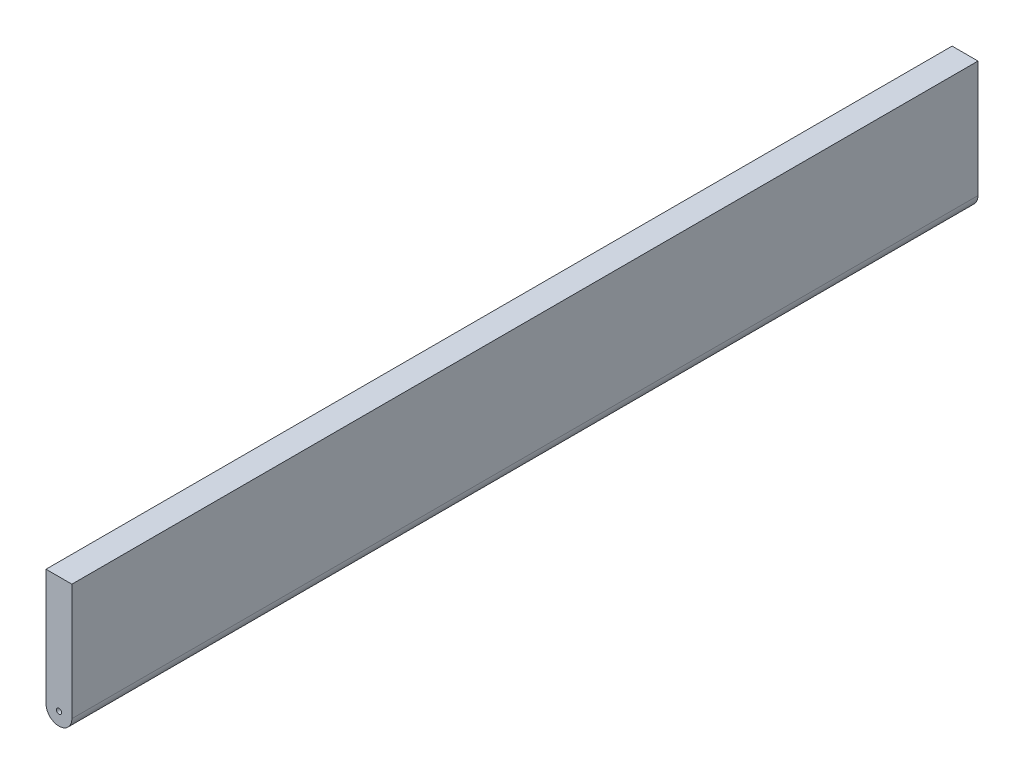
SolidWorks part; units mm, degrees
ref_plane "Front Plane" through (0, 0, 0) normal (0, 0, 1) x (1, 0, 0)
ref_plane "Top Plane" through (0, 0, 0) normal (0, 1, 0) x (1, 0, 0)
ref_plane "Right Plane" through (0, 0, 0) normal (1, 0, 0) x (0, 0, -1)
sketch "Sketch1" plane through (0, 0, 0) normal (0, 0, 1) x (1, 0, 0)
  line L2 (0, 0) -> (0, 11.43)
  line L3 (0, 11.43) -> (2.54, 11.43)
  line L4 (2.54, 0) -> (2.54, 11.43)
  arc A0 (2.54, 0) -> (0, 0) centre (1.27, 0) cw
  dimension "D3" = 1.27
  dimension "D1" = 11.43
  dimension "D2" = 2.54
extrude "Boss-Extrude1" add sketch "Sketch1" along normal blind 88.9
sketch "Sketch2" plane through (0, 0, 88.9) normal (0, 0, 1) x (1, 0, 0)
  circle A0 centre (1.27, 0) radius 0.254
  dimension "D1" = 0.508
extrude "Cut-Extrude1" cut sketch "Sketch2" against normal through all
